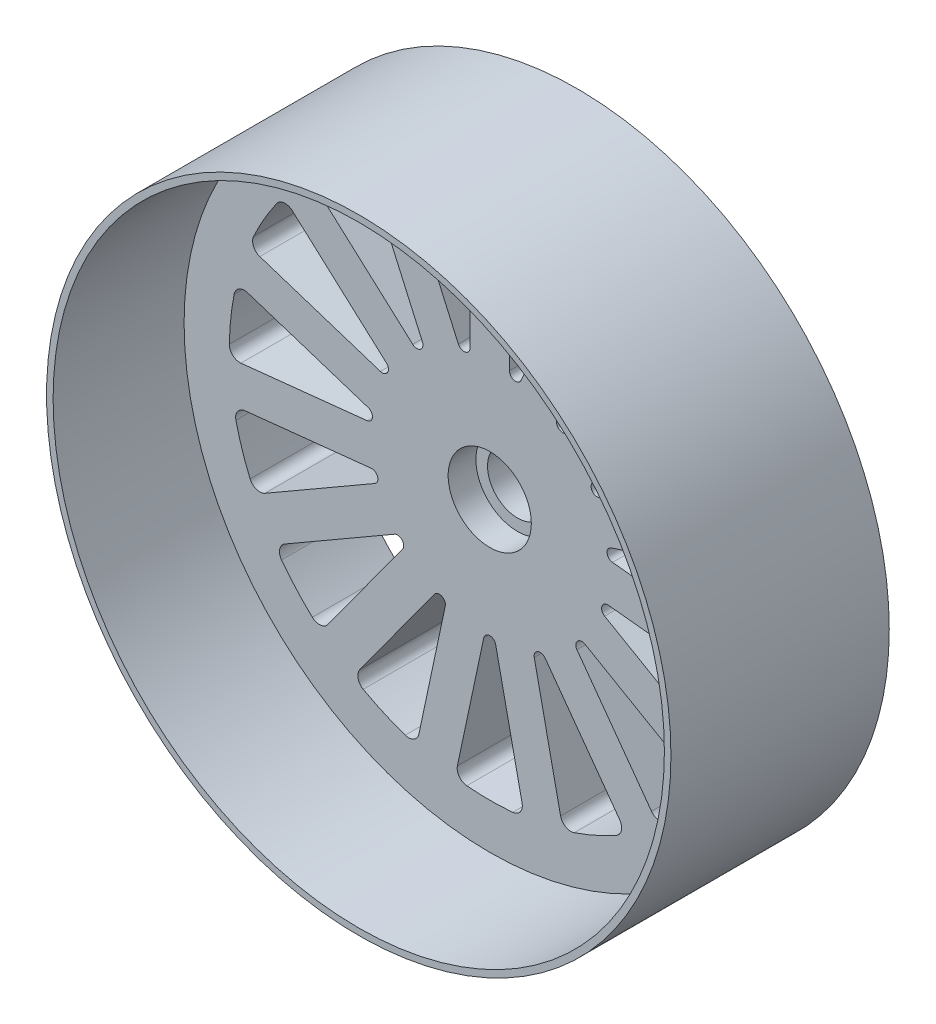
SolidWorks part; units mm, degrees
ref_plane "Front Plane" through (0, 0, 0) normal (0, 0, 1) x (1, 0, 0)
ref_plane "Top Plane" through (0, 0, 0) normal (0, 1, 0) x (1, 0, 0)
ref_plane "Right Plane" through (0, 0, 0) normal (1, 0, 0) x (0, 0, -1)
sketch "Sketch1" plane through (0, 0, 0) normal (0, 0, 1) x (1, 0, 0)
  circle A0 centre (0, 0) radius 35.75
  dimension "D1" = 71.5
extrude "OuterCase" add sketch "Sketch1" along normal blind 25
sketch "Sketch2" plane through (0, 0, 25) normal (0, 0, 1) x (1, 0, 0)
  circle A0 centre (0, 0) radius 35
  dimension "D1" = 70
extrude "Cut-Extrude1" cut sketch "Sketch2" against normal blind 15
sketch "Sketch3" plane through (0, 0, 10) normal (0, 0, 1) x (1, 0, 0)
  circle A0 centre (0, 0) radius 4.7625
  dimension "D1" = 9.525
extrude "Bearing" cut sketch "Sketch3" against normal blind 3.175
sketch "Sketch4" plane through (0, 0, 6.825) normal (0, 0, 1) x (1, 0, 0)
  circle A0 centre (0, 0) radius 3.429
  dimension "D1" = 6.858
extrude "Shaft_Room" cut sketch "Sketch4" against normal blind 5
sketch "Sketch6" plane through (0, 0, 1.825) normal (0, 0, 1) x (1, 0, 0)
  line L0 (0, 10.8241) -> (0, 29.8241) construction
  line L1 (-2.2537, 29.7388) -> (-2.2537, 10.5869)
  line L2 (2.2537, 29.7388) -> (2.2537, 10.5869)
  line L3 (14.1547, 26.2511) -> (6.3649, 8.7549)
  line L4 (10.037, 28.0844) -> (2.2472, 10.5883)
  line L5 (23.6083, 18.2243) -> (9.3756, 5.4092)
  line L6 (20.5923, 21.574) -> (6.3596, 8.7588)
  line L7 (28.9797, 7.0464) -> (10.7652, 1.1281)
  line L8 (27.5869, 11.3332) -> (9.3723, 5.4149)
  line L9 (29.3403, -5.3499) -> (10.2933, -3.348)
  line L10 (29.8115, -0.8672) -> (10.7645, 1.1347)
  line L11 (24.6277, -16.8212) -> (8.0417, -7.2452)
  line L12 (26.8814, -12.9177) -> (10.2954, -3.3417)
  line L13 (15.6568, -25.3839) -> (4.3995, -9.8897)
  line L14 (19.3033, -22.7345) -> (8.0461, -7.2403)
  line L15 (3.9786, -29.5575) -> (-0.0033, -10.8241)
  line L16 (8.3875, -28.6204) -> (4.4056, -9.887)
  line L17 (-8.3875, -28.6204) -> (-4.4056, -9.887)
  line L18 (-3.9786, -29.5575) -> (0.0033, -10.8241)
  line L19 (-19.3033, -22.7345) -> (-8.0461, -7.2403)
  line L20 (-15.6568, -25.3839) -> (-4.3995, -9.8897)
  line L21 (-26.8814, -12.9177) -> (-10.2954, -3.3417)
  line L22 (-24.6277, -16.8212) -> (-8.0417, -7.2452)
  line L23 (-29.8115, -0.8672) -> (-10.7645, 1.1347)
  line L24 (-29.3403, -5.3499) -> (-10.2933, -3.348)
  line L25 (-27.5869, 11.3332) -> (-9.3723, 5.4149)
  line L26 (-28.9797, 7.0464) -> (-10.7652, 1.1281)
  line L27 (-20.5923, 21.574) -> (-6.3596, 8.7588)
  line L28 (-23.6083, 18.2243) -> (-9.3756, 5.4092)
  line L29 (-10.037, 28.0844) -> (-2.2472, 10.5883)
  line L30 (-14.1547, 26.2511) -> (-6.3649, 8.7549)
  arc A0 (10.2933, -3.348) -> (10.2954, -3.3417) centre (0, 0) ccw
  arc A1 (29.8115, -0.8672) -> (28.9797, 7.0464) centre (0, 0) ccw
  circle A2 centre (0, 0) radius 10.8241 construction
  arc A3 (8.0417, -7.2452) -> (8.0461, -7.2403) centre (0, 0) ccw
  arc A4 (4.3995, -9.8897) -> (4.4056, -9.887) centre (0, 0) ccw
  arc A5 (-0.0033, -10.8241) -> (0.0033, -10.8241) centre (0, 0) ccw
  arc A6 (-4.4056, -9.887) -> (-4.3995, -9.8897) centre (0, 0) ccw
  arc A7 (-8.0461, -7.2403) -> (-8.0417, -7.2452) centre (0, 0) ccw
  arc A8 (-10.2954, -3.3417) -> (-10.2933, -3.348) centre (0, 0) ccw
  arc A9 (-10.7645, 1.1347) -> (-10.7652, 1.1281) centre (0, 0) ccw
  arc A10 (-9.3723, 5.4149) -> (-9.3756, 5.4092) centre (0, 0) ccw
  arc A11 (-6.3596, 8.7588) -> (-6.3649, 8.7549) centre (0, 0) ccw
  arc A12 (-2.2472, 10.5883) -> (-2.2537, 10.5869) centre (0, 0) ccw
  arc A13 (2.2537, 10.5869) -> (2.2472, 10.5883) centre (0, 0) ccw
  arc A14 (6.3649, 8.7549) -> (6.3596, 8.7588) centre (0, 0) ccw
  arc A15 (9.3756, 5.4092) -> (9.3723, 5.4149) centre (0, 0) ccw
  arc A16 (10.7652, 1.1281) -> (10.7645, 1.1347) centre (0, 0) ccw
  circle A17 centre (0, 0) radius 29.8241 construction
  arc A18 (26.8814, -12.9177) -> (29.3403, -5.3499) centre (0, 0) ccw
  arc A19 (19.3033, -22.7345) -> (24.6277, -16.8212) centre (0, 0) ccw
  arc A20 (8.3875, -28.6204) -> (15.6568, -25.3839) centre (0, 0) ccw
  arc A21 (-3.9786, -29.5575) -> (3.9786, -29.5575) centre (0, 0) ccw
  arc A22 (-15.6568, -25.3839) -> (-8.3875, -28.6204) centre (0, 0) ccw
  arc A23 (-24.6277, -16.8212) -> (-19.3033, -22.7345) centre (0, 0) ccw
  arc A24 (-29.3403, -5.3499) -> (-26.8814, -12.9177) centre (0, 0) ccw
  arc A25 (-28.9797, 7.0464) -> (-29.8115, -0.8672) centre (0, 0) ccw
  arc A26 (-23.6083, 18.2243) -> (-27.5869, 11.3332) centre (0, 0) ccw
  arc A27 (-14.1547, 26.2511) -> (-20.5923, 21.574) centre (0, 0) ccw
  arc A28 (-2.2537, 29.7388) -> (-10.037, 28.0844) centre (0, 0) ccw
  arc A29 (10.037, 28.0844) -> (2.2537, 29.7388) centre (0, 0) ccw
  arc A30 (20.5923, 21.574) -> (14.1547, 26.2511) centre (0, 0) ccw
  arc A31 (27.5869, 11.3332) -> (23.6083, 18.2243) centre (0, 0) ccw
  point P69 (0, 0)
  dimension "D1" = 19
extrude "Cut-Extrude4" cut sketch "Sketch6" along normal through all both and the other way through all contours L14 A19 L11 | L12 A18 L9 | L16 A20 L13 | L18 A21 L15 | L20 A22 L17 | L22 A23 L19 | L24 A24 L21 | L26 A25 L23 | L28 A26 L25 | L30 A27 L27 | L1 A28 L29 | L4 A29 L2 | L6 A30 L3 | L8 A31 L5 | L10 A1 L7
fillet "Fillet1" radius 0.7 15 edges at (8.0554, -7.2531, 5) (10.3091, -3.3496, 5) (10.7802, 1.133, 5) (9.3874, 5.4198, 5) (6.3714, 8.7694, 5) (2.2537, 10.6028, 5) (-2.2537, 10.6028, 5) (-6.3714, 8.7694, 5) (4.4089, -9.9025, 5) (0, -10.8396, 5) (-4.4089, -9.9025, 5) (-8.0554, -7.2531, 5) (-10.3091, -3.3496, 5) (-10.7802, 1.133, 5) (-9.3874, 5.4198, 5)
fillet "Fillet2" radius 1.2 30 edges at (-14.1547, 26.2511, 5) (-2.2537, 29.7388, 5) (10.037, 28.0844, 5) (2.2537, 29.7388, 5) (20.5923, 21.574, 5) (14.1547, 26.2511, 5) (27.5869, 11.3332, 5) (23.6083, 18.2243, 5) (29.8115, -0.8672, 5) (28.9797, 7.0464, 5) (26.8814, -12.9177, 5) (29.3403, -5.3499, 5) (24.6277, -16.8212, 5) (-23.6083, 18.2243, 5) (-27.5869, 11.3332, 5) (-20.5923, 21.574, 5) (-10.037, 28.0844, 5) (-28.9797, 7.0464, 5) (-29.8115, -0.8672, 5) (19.3033, -22.7345, 5) (15.6568, -25.3839, 5) (8.3875, -28.6204, 5) (3.9786, -29.5575, 5) (-29.3403, -5.3499, 5) (-26.8814, -12.9177, 5) (-24.6277, -16.8212, 5) (-19.3033, -22.7345, 5) (-15.6568, -25.3839, 5) (-8.3875, -28.6204, 5) (-3.9786, -29.5575, 5)
